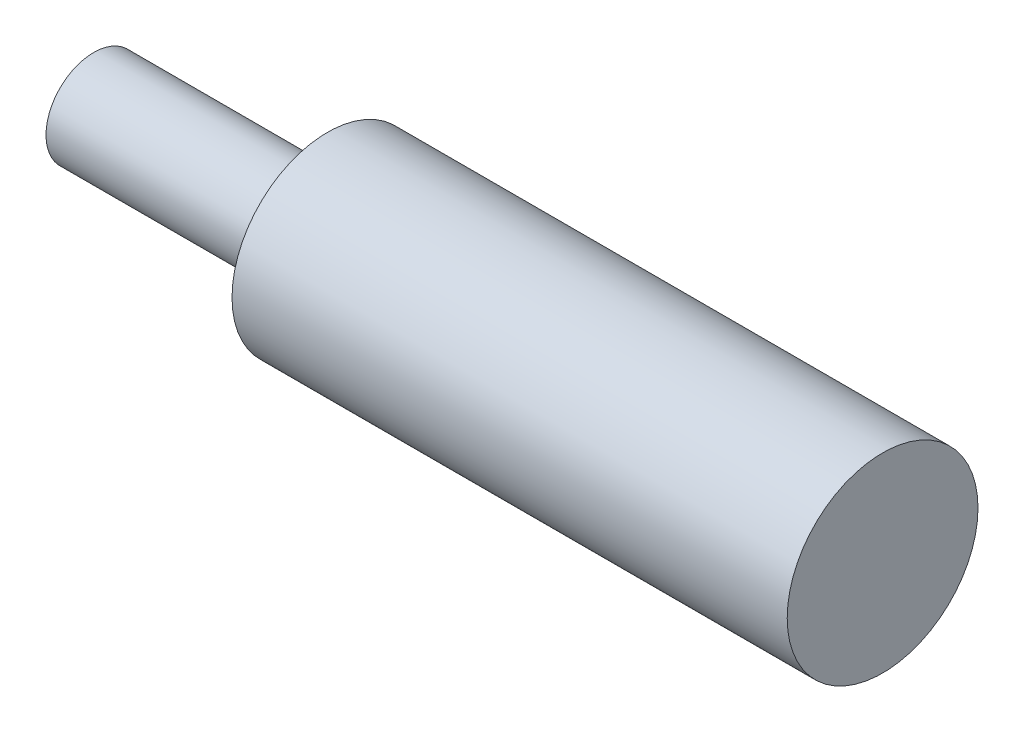
SolidWorks part; units mm, degrees
ref_plane "Front" through (0, 0, 0) normal (0, 0, 1) x (1, 0, 0)
ref_plane "Top" through (0, 0, 0) normal (0, 1, 0) x (1, 0, 0)
ref_plane "Right" through (0, 0, 0) normal (1, 0, 0) x (0, 0, -1)
sketch "Sketch3" plane through (2910.4641, 0, 0) normal (-1, 0, 0) x (0, 0, 1)
  circle A0 centre (25.3342, 11.5) radius 5 construction
  circle A1 centre (25.3342, 11.5) radius 5
extrude "Base-Extrude" add sketch "Sketch3" against normal up to surface (82.7 mm away)
sketch "Sketch4" plane through (2993.1641, 0, 0) normal (-1, 0, 0) x (0, 0, 1)
  circle A1 centre (25.3342, 11.5) radius 10 construction
  circle A2 centre (25.3342, 11.5) radius 10
extrude "Boss-Extrude1" add sketch "Sketch4" along normal up to surface (58.2 mm away)
